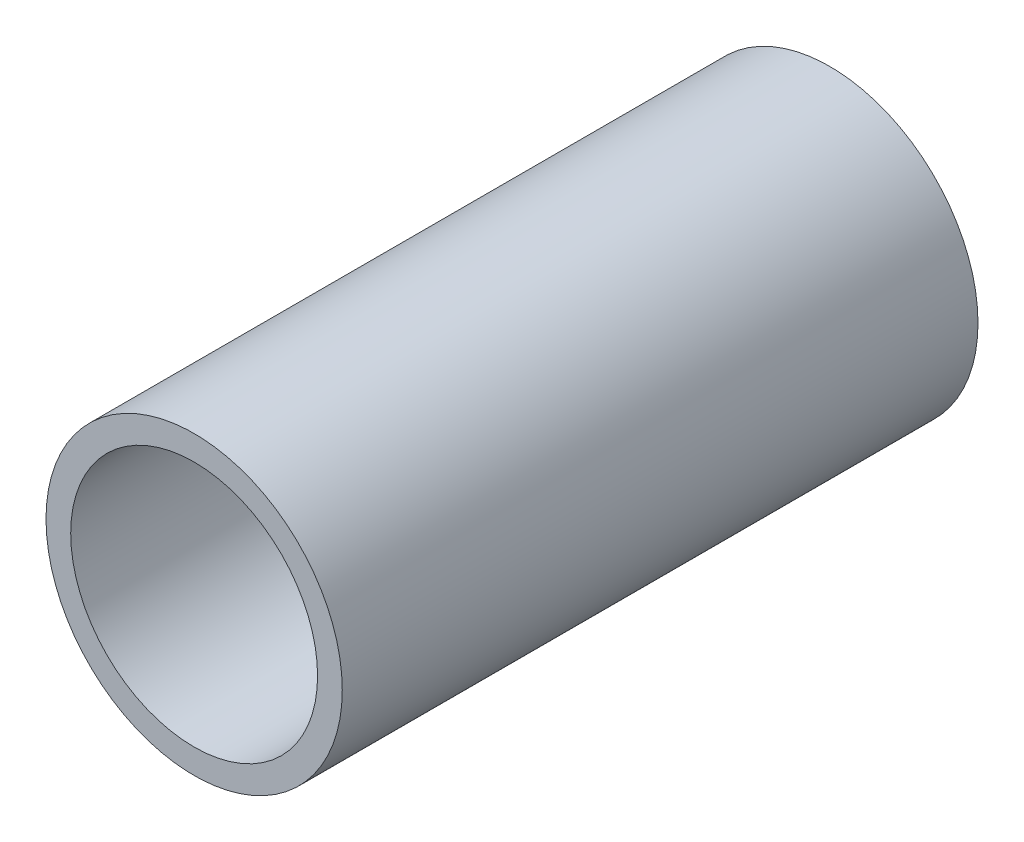
SolidWorks part; units mm, degrees
material "6061 合金"
ref_plane "前视基准面" through (0, 0, 0) normal (0, 0, 1) x (1, 0, 0)
ref_plane "上视基准面" through (0, 0, 0) normal (0, 1, 0) x (1, 0, 0)
ref_plane "右视基准面" through (0, 0, 0) normal (1, 0, 0) x (0, 0, -1)
other "Configuration Table"
sketch "草图1" plane through (0, 0, 0) normal (0, 0, 1) x (1, 0, 0)
  circle A0 centre (0, 0) radius 5
  circle A1 centre (0, 0) radius 6
  dimension "D1" = 10
  dimension "D2" = 12
extrude "凸台-拉伸1" add sketch "草图1" along normal blind 25.75 contours A0 | A1
sketch "草图2" plane through (0, 0, 0) normal (0, 0, -1) x (-1, 0, 0)
  circle A0 centre (0, 0) radius 7
  circle A1 centre (0, 0) radius 5 construction
  circle A2 centre (0, 0) radius 5
  dimension "D1" = 14
extrude "凸台-拉伸2" [suppressed] add sketch "草图2" against normal blind 1
sketch "草图3" [suppressed] plane through (0, 0, 15) normal (0, 0, 1) x (1, 0, 0)
  circle A1 centre (0, 0) radius 5 construction
  circle A2 centre (0, 0) radius 5
  circle A3 centre (0, 0) radius 7 construction
  circle A4 centre (0, 0) radius 7
extrude "凸台-拉伸3" [suppressed] add sketch "草图3" against normal blind 1
fillet "圆角1" [suppressed] radius 0.5
chamfer "倒角1" [suppressed] distance 0.2 angle 45
